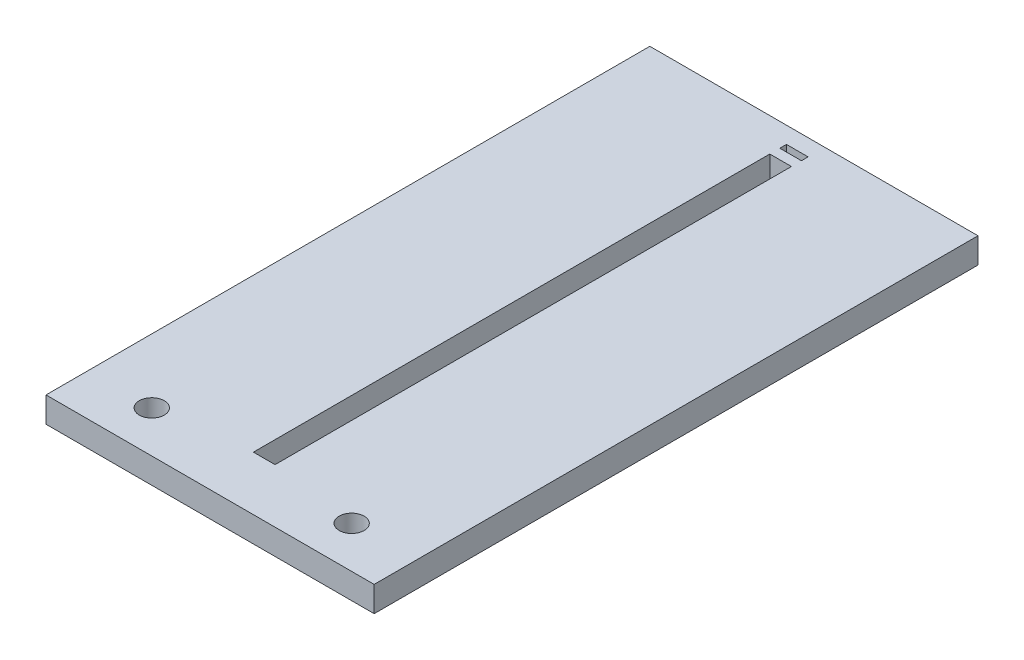
SolidWorks part; units mm, degrees
ref_plane "Front Plane" through (0, 0, 0) normal (0, 0, 1) x (1, 0, 0)
ref_plane "Top Plane" through (0, 0, 0) normal (0, 1, 0) x (1, 0, 0)
ref_plane "Right Plane" through (0, 0, 0) normal (1, 0, 0) x (0, 0, -1)
sketch "Sketch1" plane through (0, 0, 0) normal (0, 1, 0) x (1, 0, 0)
  line L1 (-19.7, 0) -> (19.7, 0)
  line L2 (-19.7, 0) -> (-19.7, 72.5)
  line L3 (-19.7, 72.5) -> (19.7, 72.5)
  line L4 (19.7, 0) -> (19.7, 72.5)
  point P5 (0, 0)
  dimension "D1" = 39.4
  dimension "D2" = 72.5
extrude "Boss-Extrude1" add sketch "Sketch1" along normal blind 3.05
sketch "Sketch4" plane through (0, 3.05, 0) normal (0, 1, 0) x (1, 0, 0)
  line L0 (-19.7, 72.5) -> (19.7, 72.5) construction
  line L2 (-19.7, 0) -> (19.7, 0) construction
  line L3 (1.3, 70.5) -> (-1.3, 70.5)
  line L4 (-1.3, 70.5) -> (-1.3, 69.7)
  line L5 (-1.3, 69.7) -> (1.3, 69.7)
  line L6 (1.3, 69.7) -> (1.3, 70.5)
  line L7 (0, 0) -> (0, 72.5) construction
  line L9 (1.3, 68.5) -> (-1.3, 68.5)
  line L10 (-1.3, 68.5) -> (-1.3, 6.5)
  line L11 (-1.3, 6.5) -> (1.3, 6.5)
  line L12 (1.3, 6.5) -> (1.3, 68.5)
  point P6 (0, 6.5)
  point P10 (0, 70.5)
  point P22 (0, 68.5)
  dimension "D1" = 2
  dimension "D2" = 0.8
  dimension "D3" = 1.2
  dimension "D4" = 2.6
  dimension "D7" = 6.5
extrude "Cut-Extrude1" cut sketch "Sketch4" against normal through all contours L5 L7 L3 L4 | L11 L7 L9 L10 | L7 L11 L12 L9 | L7 L5 L6 L3
sketch "Sketch7" plane through (0, 3.05, 0) normal (0, 1, 0) x (1, 0, 0)
  line L0 (0, 0) -> (-12, 0)
  line L1 (-19.7, 0) -> (19.7, 0) construction
  line L2 (-12, 0) -> (-12, 5)
  line L4 (0, 0) -> (0, 70) construction
  circle A0 centre (-12, 5) radius 1.5
  circle A2 centre (12, 5) radius 1.5
  dimension "D3" = 3
  dimension "D1" = 12
  dimension "D2" = 5
extrude "Cut-Extrude4" cut sketch "Sketch7" against normal through all
